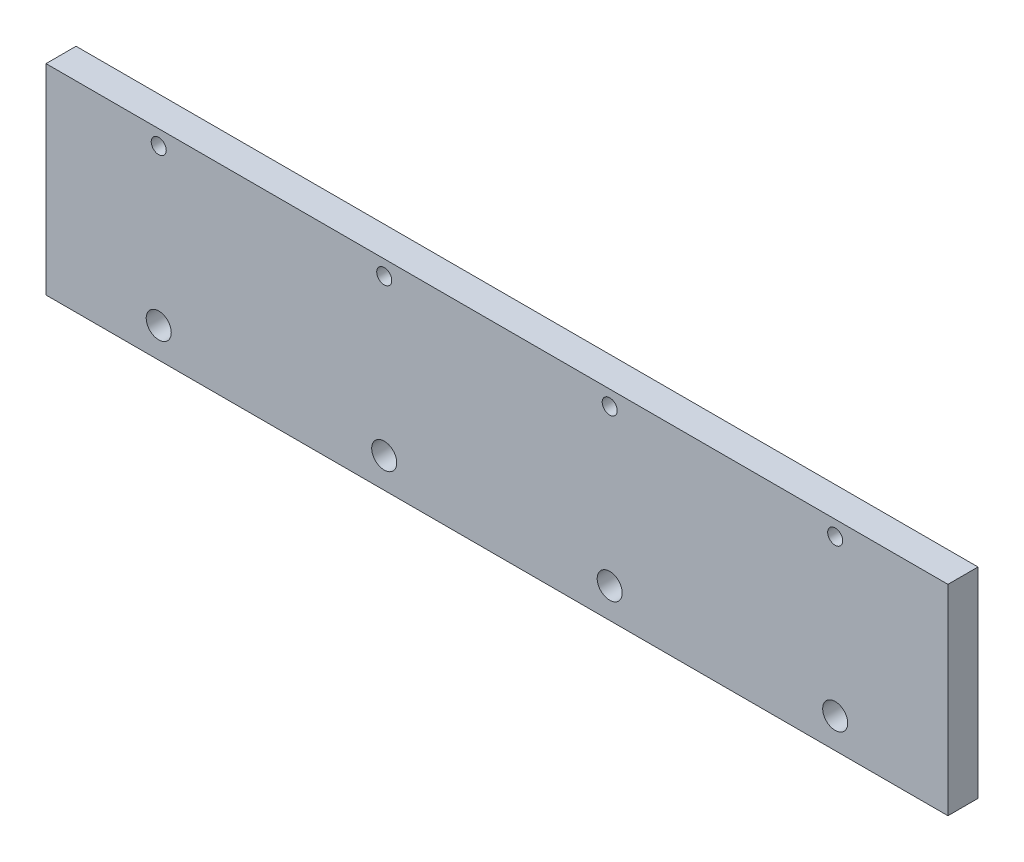
SolidWorks part; units mm, degrees
material "HDPE-green"
ref_plane "Front Plane" through (0, 0, 0) normal (0, 0, 1) x (1, 0, 0)
ref_plane "Top Plane" through (0, 0, 0) normal (0, 1, 0) x (1, 0, 0)
ref_plane "Right Plane" through (0, 0, 0) normal (1, 0, 0) x (0, 0, -1)
sketch "Sketch1" plane through (0, 0, 0) normal (0, 0, 1) x (1, 0, 0)
  line L1 (-180, -40) -> (180, -40)
  line L2 (-180, -40) -> (-180, 40)
  line L3 (-180, 40) -> (180, 40)
  line L4 (180, -40) -> (180, 40)
  line L5 (-180, -40) -> (180, 40) construction
  line L6 (-180, 40) -> (180, -40) construction
  point P0 (0, 0)
extrude "Boss-Extrude1" add sketch "Sketch1" along normal blind 12
sketch "Sketch2" plane through (0, 0, 12) normal (0, 0, 1) x (1, 0, 0)
  line L0 (-180, 40) -> (-180, -40) construction
  line L1 (180, 40) -> (-180, 40) construction
  line L2 (-180, -40) -> (180, -40) construction
  circle A0 centre (-135, 34) radius 3
  circle A1 centre (-135, -28) radius 5
  dimension "D1" = 6
  dimension "D2" = 45
  dimension "D3" = 6
  dimension "D4" = 10
  dimension "D5" = 45
  dimension "D6" = 12
extrude "Cut-Extrude1" cut sketch "Sketch2" against normal up to next
pattern_linear "LPattern1" count 4 spacing 90 along (1, 0, 0) of "Cut-Extrude1"
